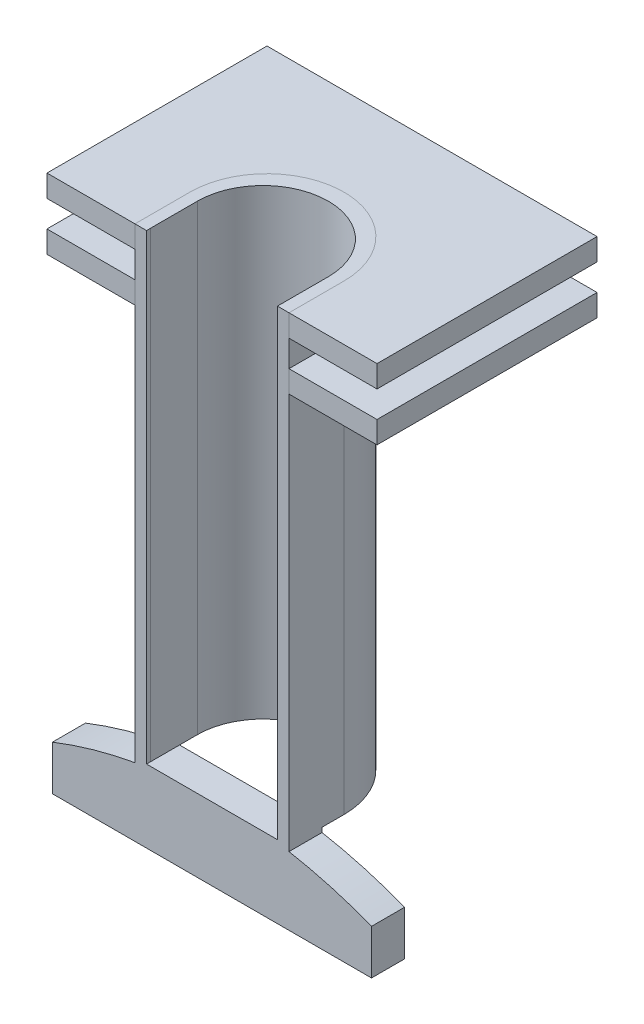
SolidWorks part; units mm, degrees
ref_plane "Front Plane" through (0, 0, 0) normal (0, 0, 1) x (1, 0, 0)
ref_plane "Top Plane" through (0, 0, 0) normal (0, 1, 0) x (1, 0, 0)
ref_plane "Right Plane" through (0, 0, 0) normal (1, 0, 0) x (0, 0, -1)
sketch "Sketch1" plane through (0, 0, 0) normal (0, 1, 0) x (1, 0, 0)
  line L0 (-7.5, 0) -> (0, 0) construction
  line L1 (0, 0) -> (0, 5) construction
  line L2 (-7, 0) -> (-7, 5)
  line L3 (7, 0) -> (7, 5)
  line L4 (0, 0) -> (0, 5) construction
  line L5 (-7, 0) -> (-7, 5)
  line L6 (7, 0) -> (7, 5)
  line L7 (0, 0.375) -> (0, 4.625) construction
  line L8 (-5.95, 0.375) -> (-5.95, 4.625)
  line L9 (5.95, 0.375) -> (5.95, 4.625)
  line L10 (-7, 0) -> (0, 0)
  line L11 (5.9382, 0) -> (7, 0)
  line L12 (0, 0) -> (5.9382, 0) construction
  line L13 (5.9382, 0) -> (7.5, 0) construction
  line L14 (0, 0) -> (5.9382, 0) construction
  arc A0 (-7, 0) -> (7, 0) centre (0, 0) ccw construction
  arc A1 (7, 5) -> (-7, 5) centre (0, 5) ccw
  arc A2 (-7, 0) -> (7, 0) centre (0, 0) ccw construction
  arc A3 (7, 5) -> (-7, 5) centre (0, 5) ccw
  arc A4 (-5.95, 0.375) -> (-5.9382, 0) centre (0, 0.375) ccw
  arc A5 (5.95, 4.625) -> (-5.95, 4.625) centre (0, 4.625) ccw
  arc A6 (5.9382, 0) -> (5.95, 0.375) centre (0, 0.375) ccw
  arc A7 (-5.9382, 0) -> (5.9382, 0) centre (0, 0.375) ccw construction
  point P6 (0, 2.5)
  point P13 (0, 2.5)
  point P20 (0, 2.5)
  dimension "D2" = 7
  dimension "D1" = 15
  dimension "D3" = 5
extrude "Boss-Extrude1" add sketch "Sketch1" along normal blind 42 contours A6 L11 L3 A1 L2 L10 A4 L8 A5 L9
sketch "Sketch2" plane through (0, 42, 0) normal (0, 1, 0) x (1, 0, 0)
  line L0 (7, 0) -> (15, 0)
  line L1 (-15, 0) -> (-7, 0)
  line L2 (-15, 0) -> (-15, 20)
  line L3 (-15, 20) -> (15, 20)
  line L4 (15, 0) -> (15, 20)
  line L5 (-7, 0) -> (7, 0) construction
  line L6 (5.9382, 0) -> (7, 0)
  line L7 (7, 0) -> (7, 5)
  line L8 (-7, 5) -> (-7, 0)
  line L9 (-7, 0) -> (-5.9382, 0)
  line L10 (-5.95, 0.375) -> (-5.95, 4.625)
  line L11 (5.95, 4.625) -> (5.95, 0.375)
  line L13 (7, 0) -> (7, 5)
  line L14 (-7, 5) -> (-7, 0)
  arc A4 (5.9382, 0) -> (5.95, 0.375) centre (0, 0.375) ccw
  arc A5 (7, 5) -> (-7, 5) centre (0, 5) ccw
  arc A6 (-5.95, 0.375) -> (-5.9382, 0) centre (0, 0.375) ccw
  arc A7 (5.95, 4.625) -> (-5.95, 4.625) centre (0, 4.625) ccw
  arc A9 (7, 5) -> (-7, 5) centre (0, 5) ccw
  dimension "D2" = 30
  dimension "D3" = 20
  dimension "D1" = 0
extrude "Boss-Extrude2" add sketch "Sketch2" against normal blind 2 separate body
sketch "Sketch3" plane through (0, 0, 0) normal (0, 0, 1) x (1, 0, 0)
  line L0 (15, -7.1153) -> (15, -2.7495) construction
  line L1 (-15, -7.1153) -> (-15, -2.7495) construction
  line L2 (-15, -7.1153) -> (15, -7.1153) construction
  line L3 (15, -7.1153) -> (15, -2.7495) construction
  line L4 (-15, -7.1153) -> (-15, -2.7495) construction
  line L5 (-15, -7.1153) -> (15, -7.1153) construction
  line L6 (7, 0) -> (7, -0.4158)
  line L7 (-7, 0) -> (-7, -0.4158)
  line L8 (-14.5, -2.5482) -> (-14.5, -6.6153)
  line L9 (-14.5, -6.6153) -> (14.5, -6.6153)
  line L10 (14.5, -6.6153) -> (14.5, -2.5482)
  line L11 (-7, 0) -> (7, 0)
  arc A0 (-15, -2.7495) -> (-14.5, -2.5482) centre (0, -39.2906) cw construction
  arc A2 (-14.5, -2.5482) -> (-7, -0.4158) centre (0, -39.2906) cw
  arc A3 (14.5, -2.5482) -> (7, -0.4158) centre (0, -39.2906) ccw
  arc A4 (15, -2.7495) -> (14.5, -2.5482) centre (0, -39.2906) ccw construction
  dimension "D3" = 39.5
  dimension "D1" = 0.5
  dimension "D2" = 0.5
  dimension "D4" = 0.5
extrude "Boss-Extrude3" add sketch "Sketch3" against normal blind 3
pattern_linear "LPattern1" count 2 spacing 4.4 along (0, -1, 0) of "Boss-Extrude2"
